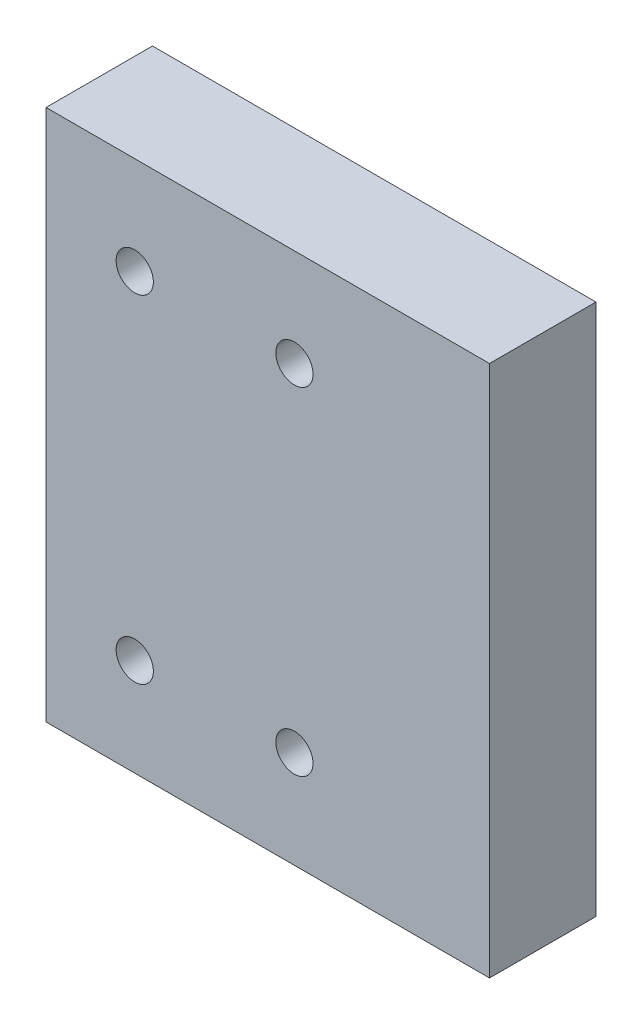
SolidWorks part; units mm, degrees
material "1.0037 (S235JR)"
ref_plane "Płaszczyzna przednia" through (0, 0, 0) normal (0, 0, 1) x (1, 0, 0)
ref_plane "Płaszczyzna górna" through (0, 0, 0) normal (0, 1, 0) x (1, 0, 0)
ref_plane "Płaszczyzna prawa" through (0, 0, 0) normal (1, 0, 0) x (0, 0, -1)
sketch "Szkic1" plane through (0, 0, 0) normal (0, 0, 1) x (1, 0, 0)
  line L0 (-8, 300) -> (-103, 300) construction
  line L1 (-8, 592) -> (-8, 8) construction
  line L2 (-8, 592) -> (-8, 8) construction
  line L3 (-53, 270) -> (-103, 270)
  line L4 (-53, 270) -> (-53, 330)
  line L5 (-53, 330) -> (-103, 330)
  line L6 (-103, 270) -> (-103, 330)
  dimension "D1" = 50
  dimension "D2" = 60
  dimension "D3" = 45
extrude "Dodanie-wyciągnięcie1" add sketch "Szkic1" along normal blind 12
hole_wizard "Otwór gwintowany M5x0.81" positions "Szkic3" profile "Szkic2" tap size "M5x0.8" standard "Ansi Metric" end condition through all
sketch "Szkic3" plane through (0, 0, 12) normal (0, 0, 1) x (1, 0, 0)
  point P0 (-93, 319)
  point P3 (-75, 319)
  point P6 (-75, 281)
  point P9 (-93, 281)
sketch "Szkic2" plane through (-93, 319, 12) normal (1, 0, 0) x (0, -1, 0)
  line L0 (0, 0) -> (0, 12)
  line L1 (0, 12) -> (2.1, 12)
  line L2 (2.1, 12) -> (2.1, 0)
  line L5 (2.1, 0) -> (0, 0)
  line L11 (0, -6.35) -> (0, 107.95) construction
  dimension "Średnica zewnętrzna gwintu" = 4.2
  dimension "Głębokość otworu gwintowanego na wylot" = 12
